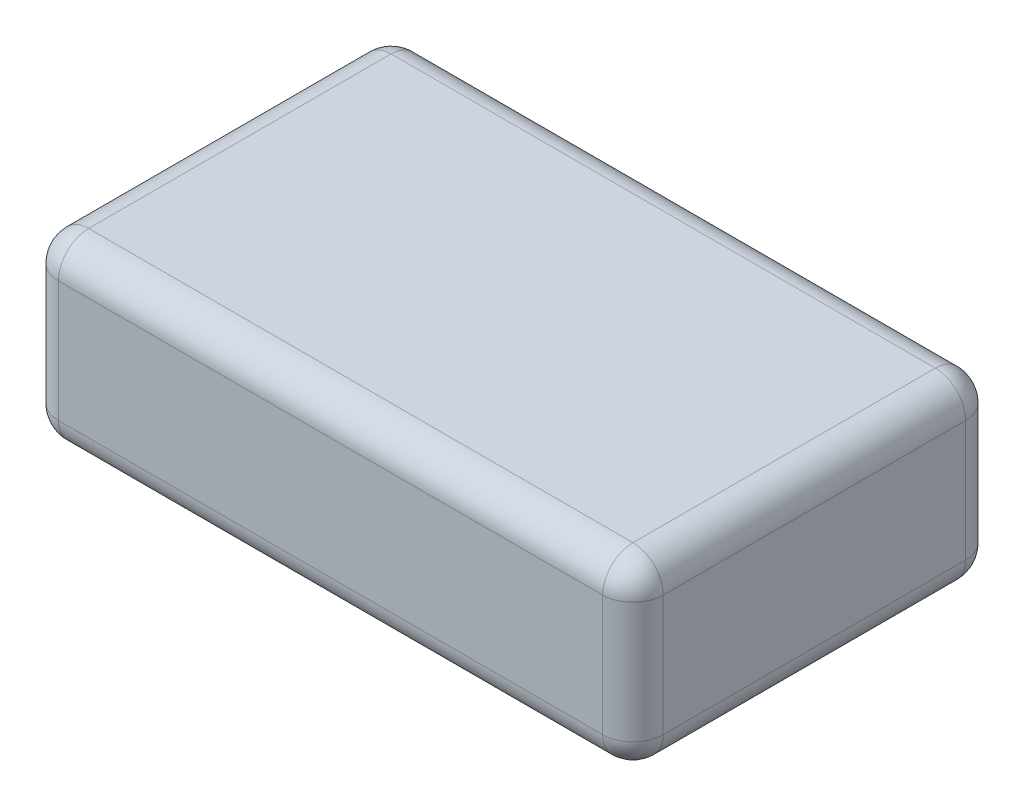
SolidWorks part; units mm, degrees
ref_plane "Front Plane" through (0, 0, 0) normal (0, 0, 1) x (1, 0, 0)
ref_plane "Top Plane" through (0, 0, 0) normal (0, 1, 0) x (1, 0, 0)
ref_plane "Right Plane" through (0, 0, 0) normal (1, 0, 0) x (0, 0, -1)
sketch "Sketch1" plane through (0, 0, 0) normal (0, 1, 0) x (1, 0, 0)
  line L1 (-100, -60) -> (100, -60)
  line L2 (-100, -60) -> (-100, 60)
  line L3 (-100, 60) -> (100, 60)
  line L4 (100, -60) -> (100, 60)
  line L5 (-100, -60) -> (100, 60) construction
  line L6 (-100, 60) -> (100, -60) construction
  point P0 (0, 0)
  dimension "D1" = 200
  dimension "D2" = 120
extrude "Boss-Extrude1" add sketch "Sketch1" along normal blind 60
fillet "Fillet1" radius 10 12 edges at (-100, 30, 60) (0, 60, 60) (-100, 60, 0) (-100, 0, 0) (0, 0, 60) (0, 60, -60) (-100, 30, -60) (0, 0, -60) (100, 30, 60) (100, 60, 0) (100, 30, -60) (100, 0, 0)
